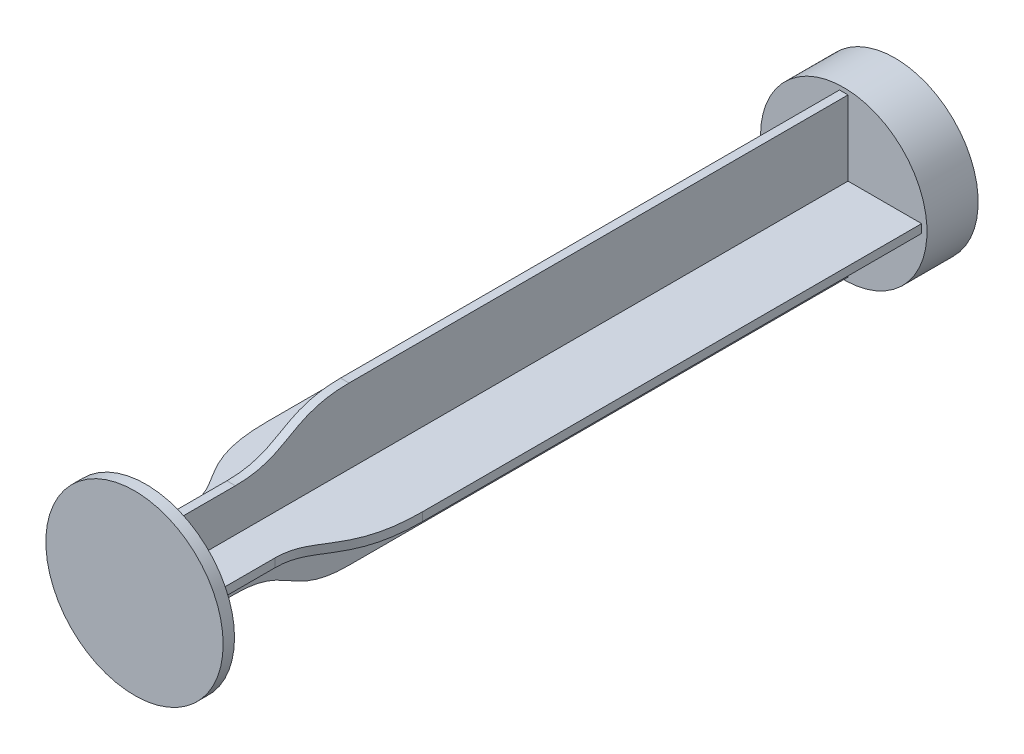
SolidWorks part; units mm, degrees
ref_plane "Front Plane" through (0, 0, 0) normal (0, 0, 1) x (1, 0, 0)
ref_plane "Top Plane" through (0, 0, 0) normal (0, 1, 0) x (1, 0, 0)
ref_plane "Right Plane" through (0, 0, 0) normal (1, 0, 0) x (0, 0, -1)
sketch "Sketch1" plane through (0, 0, 0) normal (0, 0, 1) x (1, 0, 0)
  circle A0 centre (0, 0) radius 15.6
  dimension "D1" = 31.2
extrude "Boss-Extrude1" add sketch "Sketch1" along normal blind 2
ref_plane "Plane1" through (0, 0, -122.8) normal (0, 0, -1) x (-1, 0, 0)
sketch "Sketch5" plane through (0, 0, -122.8) normal (0, 0, -1) x (-1, 0, 0)
  line L0 (0.75, 0.75) -> (13.7, 0.75)
  line L1 (-0.75, -13.8863) -> (0.75, -13.8863)
  line L2 (-0.75, -13.8863) -> (-0.75, -0.75)
  line L3 (-0.75, 13.8863) -> (0.75, 13.8863)
  line L4 (0.75, -13.8863) -> (0.75, -0.75)
  line L5 (-0.75, -13.8863) -> (0.75, 13.8863) construction
  line L6 (-0.75, 13.8863) -> (0.75, -13.8863) construction
  line L7 (-13.7, -0.75) -> (-0.75, -0.75)
  line L8 (-13.7, -0.75) -> (-13.7, 0.75)
  line L9 (-13.7, 0.75) -> (-0.75, 0.75)
  line L10 (13.7, -0.75) -> (13.7, 0.75)
  line L11 (-13.7, -0.75) -> (13.7, 0.75) construction
  line L12 (-13.7, 0.75) -> (13.7, -0.75) construction
  line L13 (0.75, -0.75) -> (13.7, -0.75)
  line L14 (0.75, 0.75) -> (0.75, 13.8863)
  line L16 (-0.75, 0.75) -> (-0.75, 13.8863)
  circle A0 centre (0, 0) radius 15.6 construction
  circle A1 centre (0, 0) radius 15.6 construction
  point P0 (0, 0)
  point P6 (0, 0)
  point P17 (0, 13.8863)
  point P18 (13.7, 0)
  dimension "D1" = 27.4
  dimension "D2" = 1.5
extrude "Boss-Extrude3" add sketch "Sketch5" against normal up to surface (122.8 mm away) up to face at (15.6, 0, 0)
sketch "Sketch11" plane through (0, 0, -122.8) normal (0, 0, -1) x (-1, 0, 0)
  circle A0 centre (0, 0) radius 14.65
  dimension "D1" = 29.3
extrude "Boss-Extrude4" add sketch "Sketch11" along normal blind 9
sketch "Sketch12" plane through (-0.75, 0, 0) normal (-1, 0, 0) x (0, 0, 1)
  line L0 (0, 8.228) -> (-15, 8.228)
  line L1 (0, 15.6) -> (0, -15.6) construction
  line L2 (-15, 8.228) -> (-24.4896, 8.228) construction
  line L3 (-35, 13.8863) -> (-35, 19.5209)
  line L4 (-24.4896, 8.228) -> (-24.4896, 13.8863) construction
  line L5 (-24.4896, 13.8863) -> (-35, 13.8863) construction
  line L6 (0, 13.8863) -> (-122.8, 13.8863) construction
  line L7 (-35, 19.5209) -> (0, 19.5209)
  line L8 (0, 19.5209) -> (0, 8.228)
  line L9 (0, 0) -> (-21.0204, 0) construction
  line L10 (-15, -8.228) -> (-24.4896, -8.228) construction
  line L11 (-24.4896, -8.228) -> (-24.4896, -13.8863) construction
  line L12 (-24.4896, -13.8863) -> (-35, -13.8863) construction
  line L13 (0, -19.5209) -> (0, -8.228)
  line L14 (-35, -19.5209) -> (0, -19.5209)
  line L15 (-35, -13.8863) -> (-35, -19.5209)
  line L16 (0, -8.228) -> (-15, -8.228)
  spline S0 degree 3 poles (-15, 8.228) (-24.4896, 8.228) (-24.4896, 13.8863) (-35, 13.8863) knots 0 0 0 0 1 1 1 1
  spline S1 degree 3 poles (-15, -8.228) (-24.4896, -8.228) (-24.4896, -13.8863) (-35, -13.8863) knots 0 0 0 0 1 1 1 1
  dimension "D1" = 20
  dimension "D2" = 15
extrude "Cut-Extrude1" cut sketch "Sketch12" against normal up to surface (1.5 mm away) contours L8 L0 S0 L3 L7 | S1 L15 L14 L13 L16 up to face at (0.75, 7.3182, -61.4)
sketch "Sketch13" plane through (0, -0.75, 0) normal (0, -1, 0) x (1, 0, 0)
  line L0 (0, 0) -> (0, -10.303) construction
  line L1 (7.75, 0) -> (7.75, -15)
  line L2 (-15.6, 0) -> (15.6, 0) construction
  line L3 (7.75, -15) -> (7.75, -21.9667) construction
  line L4 (7.75, -21.9667) -> (13.7, -21.9667) construction
  line L5 (13.7, -21.9667) -> (13.7, -35) construction
  line L6 (13.7, 0) -> (13.7, -122.8) construction
  line L7 (13.7, -35) -> (21.1107, -35)
  line L8 (21.1107, -35) -> (21.1107, 0)
  line L9 (21.1107, 0) -> (7.75, 0)
  line L10 (-7.75, -15) -> (-7.75, -21.9667) construction
  line L11 (-7.75, -21.9667) -> (-13.7, -21.9667) construction
  line L12 (-13.7, -21.9667) -> (-13.7, -35) construction
  line L13 (-21.1107, 0) -> (-7.75, 0)
  line L14 (-21.1107, -35) -> (-21.1107, 0)
  line L15 (-13.7, -35) -> (-21.1107, -35)
  line L16 (-7.75, 0) -> (-7.75, -15)
  spline S0 degree 3 poles (7.75, -15) (7.75, -21.9667) (13.7, -21.9667) (13.7, -35) knots 0 0 0 0 1 1 1 1
  spline S1 degree 3 poles (-7.75, -15) (-7.75, -21.9667) (-13.7, -21.9667) (-13.7, -35) knots 0 0 0 0 1 1 1 1
  dimension "D1" = 7.75
  dimension "D2" = 15
  dimension "D3" = 20
extrude "Cut-Extrude2" cut sketch "Sketch13" against normal up to surface (1.5 mm away) contours L9 L1 S0 L7 L8 | S1 L15 L14 L13 L16 up to face at (7.225, 0.75, -61.4)
